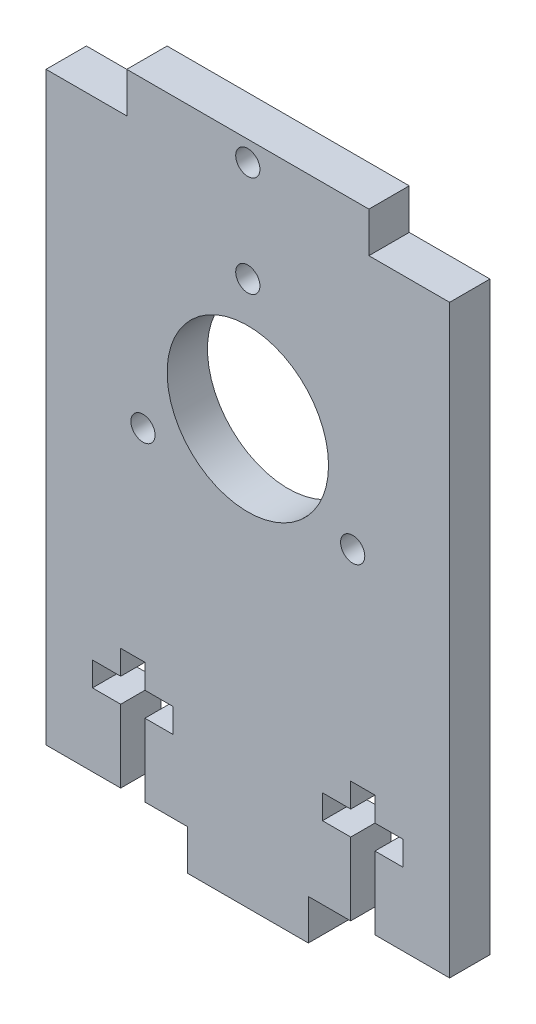
SolidWorks part; units mm, degrees
material "CA"
ref_plane "Alzado" through (0, 0, 0) normal (0, 0, 1) x (1, 0, 0)
ref_plane "Planta" through (0, 0, 0) normal (0, 1, 0) x (1, 0, 0)
ref_plane "Vista lateral" through (0, 0, 0) normal (1, 0, 0) x (0, 0, -1)
sketch "Croquis1" plane through (0, 0, 0) normal (0, 0, 1) x (1, 0, 0)
  line L0 (0, 0) -> (9.25, 0)
  line L1 (9.25, 0) -> (9.25, 9)
  line L2 (9.25, 9) -> (5.75, 9)
  line L3 (5.75, 9) -> (5.75, 12)
  line L4 (5.75, 12) -> (9.25, 12)
  line L5 (9.25, 12) -> (9.25, 15)
  line L6 (9.25, 15) -> (12.25, 15)
  line L7 (12.25, 15) -> (12.25, 12)
  line L8 (12.25, 12) -> (15.75, 12)
  line L9 (15.75, 12) -> (15.75, 9)
  line L10 (15.75, 9) -> (12.25, 9)
  line L11 (12.25, 9) -> (12.25, 0)
  line L12 (12.25, 0) -> (17.5, 0)
  line L13 (17.5, 0) -> (17.5, -5)
  line L14 (17.5, -5) -> (32.5, -5)
  line L15 (0, 72.5) -> (10, 72.5)
  line L16 (0, 0) -> (0, 72.5)
  line L17 (50, 0) -> (50, 72.5)
  line L18 (32.5, 0) -> (32.5, -5)
  line L19 (37.75, 0) -> (32.5, 0)
  line L20 (37.75, 9) -> (37.75, 0)
  line L21 (34.25, 9) -> (37.75, 9)
  line L22 (34.25, 12) -> (34.25, 9)
  line L23 (37.75, 12) -> (34.25, 12)
  line L24 (37.75, 15) -> (37.75, 12)
  line L25 (40.75, 15) -> (37.75, 15)
  line L26 (40.75, 12) -> (40.75, 15)
  line L27 (44.25, 12) -> (40.75, 12)
  line L28 (44.25, 9) -> (44.25, 12)
  line L29 (40.75, 9) -> (44.25, 9)
  line L30 (40.75, 0) -> (40.75, 9)
  line L31 (50, 0) -> (40.75, 0)
  line L32 (10, 72.5) -> (10, 77.5)
  line L33 (10, 77.5) -> (40, 77.5)
  line L34 (40, 77.5) -> (40, 72.5)
  line L35 (40, 72.5) -> (50, 72.5)
  circle A0 centre (25, 75) radius 1.5
  circle A1 centre (25, 47.5) radius 10
  circle A2 centre (25, 62.5) radius 1.5
  circle A3 centre (37.9904, 40) radius 1.5
  circle A4 centre (12.0096, 40) radius 1.5
  point P50 (25, 47.5)
  dimension "D31" = 3
  dimension "D32" = 5
  dimension "D1" = 9.25
  dimension "D2" = 9
  dimension "D3" = 3
  dimension "D4" = 3.5
  dimension "D5" = 3.5
  dimension "D6" = 3
  dimension "D7" = 3
  dimension "D8" = 3
  dimension "D9" = 3.5
  dimension "D10" = 5.25
  dimension "D11" = 10
  dimension "D12" = 15
  dimension "D13" = 72.5
  dimension "D14" = 30
  dimension "D15" = 50
  dimension "D16" = 9.25
  dimension "D17" = 5.25
  dimension "D18" = 3
  dimension "D19" = 3
  dimension "D20" = 3
  dimension "D21" = 3.5
  dimension "D22" = 3.5
  dimension "D23" = 3.5
  dimension "D24" = 3.5
  dimension "D25" = 3
  dimension "D26" = 3
  dimension "D27" = 5
  dimension "D28" = 72.5
  dimension "D29" = 5
  dimension "D30" = 3
extrude "Saliente-Extruir1" add sketch "Croquis1" along normal blind 5
